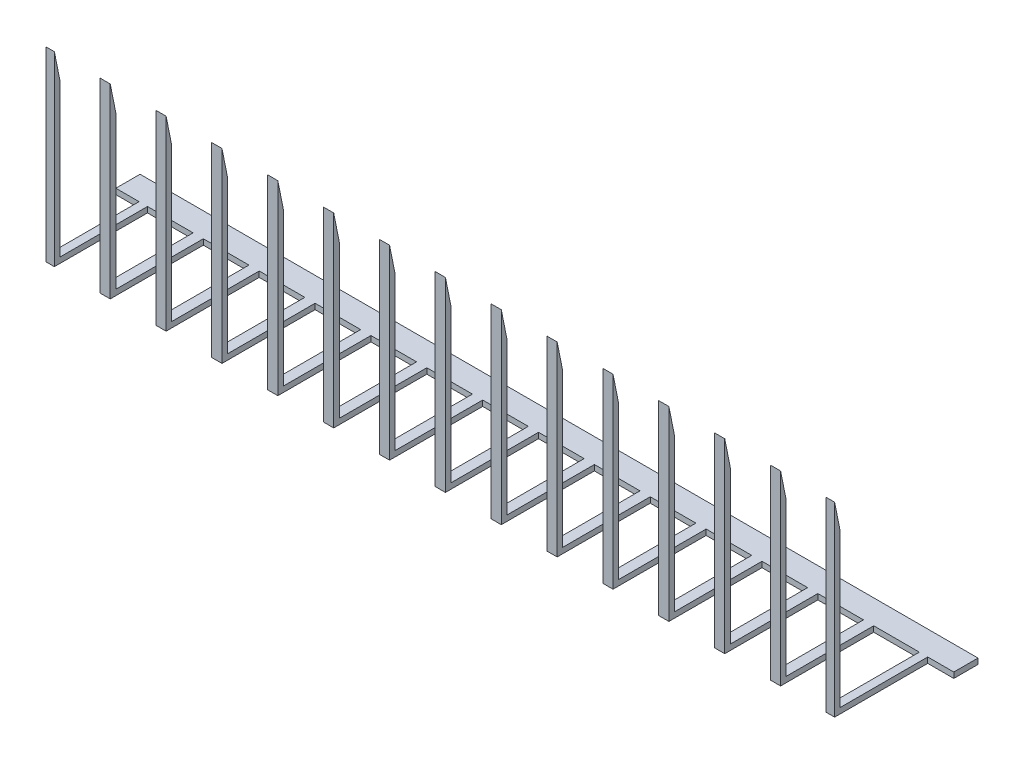
SolidWorks part; units mm, degrees
ref_plane "前视基准面" through (0, 0, 0) normal (0, 0, 1) x (1, 0, 0)
ref_plane "上视基准面" through (0, 0, 0) normal (0, 1, 0) x (1, 0, 0)
ref_plane "右视基准面" through (0, 0, 0) normal (1, 0, 0) x (0, 0, -1)
sketch "草图1" plane through (0, 0, 0) normal (0, 1, 0) x (1, 0, 0)
  line L1 (0, 0) -> (450, 0)
  line L2 (0, 0) -> (0, 60)
  line L3 (0, 60) -> (450, 60)
  line L4 (450, 0) -> (450, 60)
  dimension "D1" = 450
  dimension "D2" = 60
extrude "凸台-拉伸1" add sketch "草图1" along normal blind 3
sketch "草图2" plane through (0, 0, 0) normal (0, 0, 1) x (1, 0, 0)
  line L1 (0, 0) -> (450, 0)
  line L2 (0, 0) -> (0, 100)
  line L3 (0, 100) -> (450, 100)
  line L4 (450, 0) -> (450, 100)
  dimension "D1" = 100
extrude "凸台-拉伸2" add sketch "草图2" along normal blind 3
sketch "草图3" plane through (0, 0, 0) normal (0, -1, 0) x (1, 0, 0)
  line L0 (0, 3) -> (450, 3) construction
  line L1 (450, 3) -> (436, 3)
  line L2 (450, 3) -> (450, -47)
  line L3 (450, -47) -> (436, -47)
  line L4 (436, 3) -> (436, -47)
  line L5 (431.5, 3) -> (407, 3)
  line L6 (431.5, 3) -> (431.5, -47)
  line L7 (431.5, -47) -> (407, -47)
  line L8 (407, 3) -> (407, -47)
  line L9 (401.5, 3) -> (401.5, -47)
  line L10 (401.5, -47) -> (377, -47)
  line L11 (377, 3) -> (377, -47)
  line L12 (401.5, 3) -> (377, 3)
  line L13 (371.5, 3) -> (371.5, -47)
  line L14 (371.5, -47) -> (347, -47)
  line L15 (347, 3) -> (347, -47)
  line L16 (371.5, 3) -> (347, 3)
  line L17 (341.5, 3) -> (341.5, -47)
  line L18 (341.5, -47) -> (317, -47)
  line L19 (317, 3) -> (317, -47)
  line L20 (341.5, 3) -> (317, 3)
  line L21 (311.5, 3) -> (311.5, -47)
  line L22 (311.5, -47) -> (287, -47)
  line L23 (287, 3) -> (287, -47)
  line L24 (311.5, 3) -> (287, 3)
  line L25 (281.5, 3) -> (281.5, -47)
  line L26 (281.5, -47) -> (257, -47)
  line L27 (257, 3) -> (257, -47)
  line L28 (281.5, 3) -> (257, 3)
  line L29 (251.5, 3) -> (251.5, -47)
  line L30 (251.5, -47) -> (227, -47)
  line L31 (227, 3) -> (227, -47)
  line L32 (251.5, 3) -> (227, 3)
  line L33 (221.5, 3) -> (221.5, -47)
  line L34 (221.5, -47) -> (197, -47)
  line L35 (197, 3) -> (197, -47)
  line L36 (221.5, 3) -> (197, 3)
  line L37 (191.5, 3) -> (191.5, -47)
  line L38 (191.5, -47) -> (167, -47)
  line L39 (167, 3) -> (167, -47)
  line L40 (191.5, 3) -> (167, 3)
  line L41 (161.5, 3) -> (161.5, -47)
  line L42 (161.5, -47) -> (137, -47)
  line L43 (137, 3) -> (137, -47)
  line L44 (161.5, 3) -> (137, 3)
  line L45 (131.5, 3) -> (131.5, -47)
  line L46 (131.5, -47) -> (107, -47)
  line L47 (107, 3) -> (107, -47)
  line L48 (131.5, 3) -> (107, 3)
  line L49 (101.5, 3) -> (101.5, -47)
  line L50 (101.5, -47) -> (77, -47)
  line L51 (77, 3) -> (77, -47)
  line L52 (101.5, 3) -> (77, 3)
  line L53 (71.5, 3) -> (71.5, -47)
  line L54 (71.5, -47) -> (47, -47)
  line L55 (47, 3) -> (47, -47)
  line L56 (71.5, 3) -> (47, 3)
  line L57 (41.5, 3) -> (41.5, -47)
  line L58 (41.5, -47) -> (17, -47)
  line L59 (17, 3) -> (17, -47)
  line L60 (41.5, 3) -> (17, 3)
  line L62 (0, 3) -> (12.5, 3)
  line L63 (0, 3) -> (0, -47)
  line L64 (0, -47) -> (12.5, -47)
  line L65 (12.5, 3) -> (12.5, -47)
  dimension "D1" = 14
  dimension "D2" = 50
  dimension "D3" = 24.5
  dimension "D4" = 4.5
  dimension "D6" = 4.5
  dimension "D5" = 14
sketch "草图6" plane through (450, 0, 0) normal (1, 0, 0) x (0, 0, -1)
  line L0 (-3, 100) -> (0, 85)
  line L1 (0, 3) -> (0, 100) construction
  line L2 (0, 85) -> (0, 100)
  line L3 (0, 100) -> (-3, 100)
  dimension "D1" = 15
extrude "切除-拉伸2" cut sketch "草图6" against normal through all
extrude "切除-拉伸3" cut sketch "草图3" against normal through all
